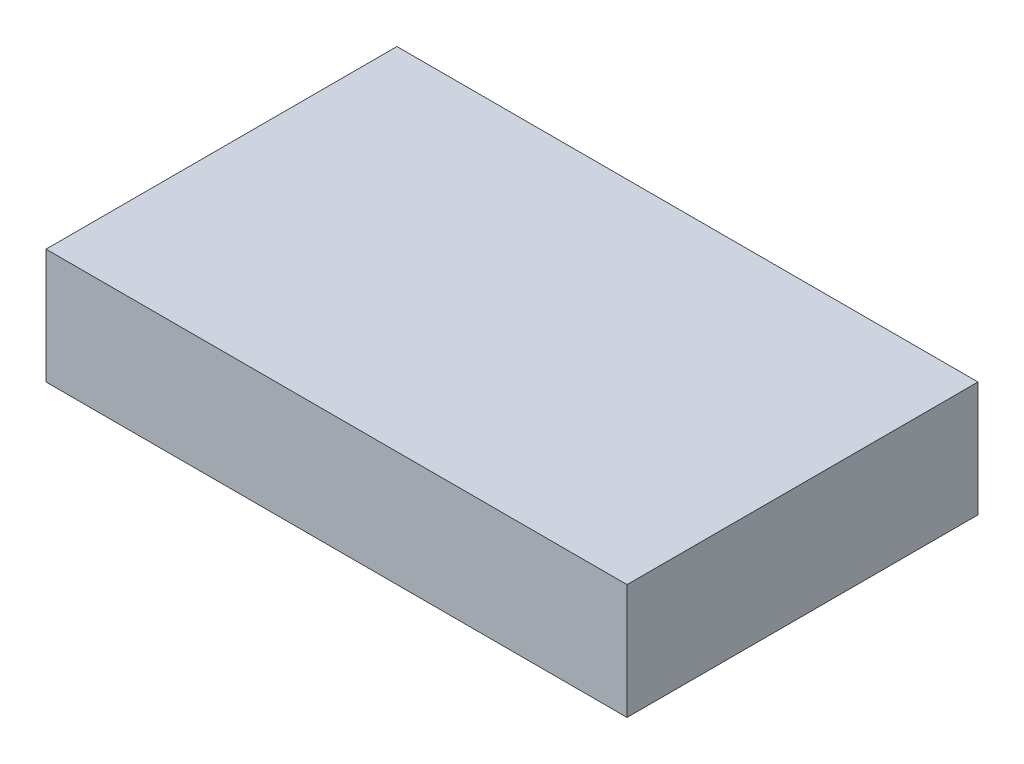
SolidWorks part; units mm, degrees
ref_plane "Front Plane" through (0, 0, 0) normal (0, 0, 1) x (1, 0, 0)
ref_plane "Top Plane" through (0, 0, 0) normal (0, 1, 0) x (1, 0, 0)
ref_plane "Right Plane" through (0, 0, 0) normal (1, 0, 0) x (0, 0, -1)
sketch "Sketch1" plane through (0, 0, 0) normal (0, 1, 0) x (1, 0, 0)
  line L1 (-5.05, 3.05) -> (5.05, 3.05)
  line L2 (-5.05, 3.05) -> (-5.05, -3.05)
  line L3 (-5.05, -3.05) -> (5.05, -3.05)
  line L4 (5.05, 3.05) -> (5.05, -3.05)
  line L5 (-5.05, 3.05) -> (5.05, -3.05) construction
  line L6 (-5.05, -3.05) -> (5.05, 3.05) construction
  point P0 (0, 0)
  dimension "D1" = 6.1
  dimension "D2" = 10.1
extrude "Boss-Extrude1" add sketch "Sketch1" along normal blind 2
